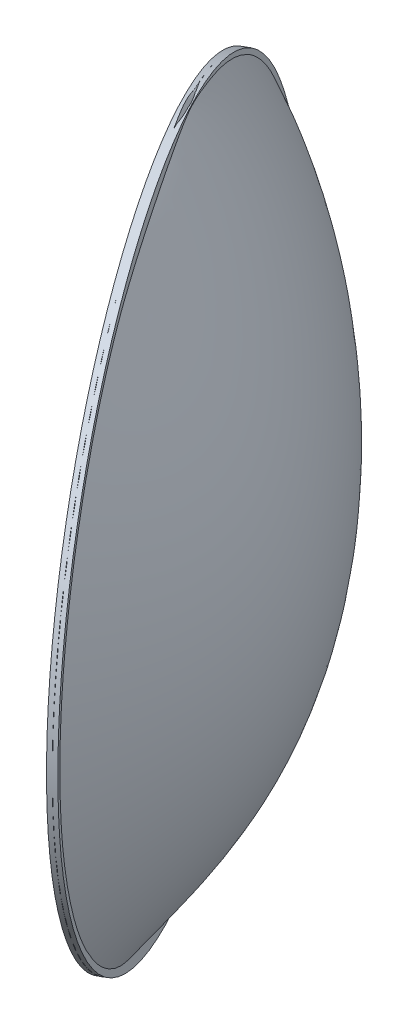
SolidWorks part; units mm, degrees
ref_plane "Front Plane" through (0, 0, 0) normal (0, 0, 1) x (1, 0, 0)
ref_plane "Top Plane" through (0, 0, 0) normal (0, 1, 0) x (1, 0, 0)
ref_plane "Right Plane" through (0, 0, 0) normal (1, 0, 0) x (0, 0, -1)
sketch "Sketch1" plane through (0, 0, 0) normal (1, 0, 0) x (0, 0, -1)
  circle A0 centre (0, 0) radius 40
  dimension "D1" = 80
extrude "Boss-Extrude1" add sketch "Sketch1" along normal blind 1
sketch "Sketch2" plane through (1, 0, 0) normal (1, 0, 0) x (0, 0, -1)
  arc A0 (-19.162, 35.1115) -> (-19.162, -35.1115) centre (0, 0) ccw
  circle A1 centre (0, 0) radius 40 construction
  arc A2 (6.8395, 39.4109) -> (6.8395, -39.4109) centre (0, 0) cw
sketch "Sketch3" plane through (0, 0, 0) normal (0, 0, 1) x (1, 0, 0)
  line L0 (1, -40) -> (1, 40) construction
  arc A0 (1, 40) -> (1, -40) centre (-45, 0) cw
  dimension "D1" = 45
surface "Surface-Loft1"
sketch "Sketch5" plane through (0, 0, 0) normal (-1, 0, 0) x (0, 0, 1)
  circle A0 centre (0, 0) radius 9
  dimension "D1" = 18
surface "Surface-Trim1" [suppressed]
ref_plane "Plane1" through (10, 0, 0) normal (-1, 0, 0) x (0, 0, 1)
sketch "Sketch6" [suppressed] plane through (0, 0, 0) normal (0, 0, 1) x (1, 0, 0)
  line L0 (0, 0) -> (15.5766, 0)
  spline S0 degree 3 poles (15.5732, -1.7731) (15.5782, -0.0014) (15.5732, 1.7707) (15.5584, 3.4708) (15.5342, 5.0374) (15.5012, 6.4089) (15.4598, 7.5344) (15.4105, 8.3707) (15.3541, 8.8846) (15.2915, 9.0579) (15.225, 8.8837) (15.1567, 8.368) (15.0896, 7.5316) (15.0274, 6.4058) (14.9738, 5.0333) (14.9327, 3.4691) (14.9069, 1.7691) (14.8981, 0.0026) (14.9068, -1.7652) (14.9326, -3.4651) (14.9737, -5.0301) (15.0272, -6.4034) (15.0894, -7.5289) (15.1566, -8.3665) (15.2249, -8.8828) (15.2914, -9.0579) (15.354, -8.8854) (15.4104, -8.3721) (15.4597, -7.5365) (15.5011, -6.4124) (15.5341, -5.0407) (15.5583, -3.4751) (15.5732, -1.7731) (15.5782, -0.0014) (15.5732, 1.7707) knots -0.093901 -0.062673 -0.031358 0 0.031281 0.062626 0.09378 0.125079 0.15632 0.187522 0.218839 0.249983 0.281308 0.312489 0.343752 0.375034 0.406199 0.437527 0.468675 0.499981 0.531208 0.562424 0.593736 0.624883 0.656209 0.687383 0.718656 0.74993 0.781102 0.812428 0.843573 0.874885 0.906099 0.937327 0.968642 1 1.031281 1.062626 1.09378 only from (15.5766, 0) to (15.5766, 0) construction
  dimension "D1" = 15.5766
ref_plane "Plane2" through (15.5766, 0, 0) normal (-1, 0, 0) x (0, 0, 1)
ref_plane "Plane3" through (50, 0, 0) normal (-1, 0, 0) x (0, 0, 1)
sketch "Sketch8" plane through (50, 0, 0) normal (-1, 0, 0) x (0, 0, 1)
  circle A0 centre (0, 0) radius 12
  circle A1 centre (0, 0) radius 10
  arc A2 (-2.5, -9.6825) -> (2.5, -9.6825) centre (0, 0) ccw
  arc A3 (-2.5, -11.7367) -> (2.5, -11.7367) centre (0, 0) ccw
  dimension "D1" = 20
  dimension "D2" = 24
surface "Surface-Trim2" [suppressed]
sketch "Sketch9" plane through (50, 0, 0) normal (-1, 0, 0) x (0, 0, 1)
  line L0 (-2.5, -9.6825) -> (-2.5, -11.7367)
  line L2 (1.4947, -11.9065) -> (1.4947, -9.8877)
  arc A0 (-2.5, -9.6825) -> (1.4947, -9.8877) centre (0, 0) ccw
  arc A1 (-2.5, -11.7367) -> (1.4947, -11.9065) centre (0, 0) ccw
  dimension "D1" = 20
  dimension "D2" = 24
  dimension "D3" = 4
extrude "Boss-Extrude2" [suppressed] add sketch "Sketch9" along normal blind 3 separate body
pattern_circular "CirPattern3" [suppressed] count 10 over 360
move or copy body "Body-Move/Copy1" [suppressed] placed by mates yes parameters "D1"=0, "D2"=0, "D3"=0
other "Distance4" [suppressed] parameters "D1"=11
scale "Scale1" bodies to scale 101 102 scale about centroid uniform scaling yes scale factor 0.5
move or copy body "Body-Move/Copy2" bodies to move or copy 129 copy no translate (4.1711, 0, 0) parameters "D1"=4.1711, "D2"=0, "D3"=0
move or copy body "Body-Move/Copy3" bodies to move or copy 130 131 copy no rotation origin (7.2384, 0, -0.0388) rotation axis (0, 1, 0) rotation angle 30
